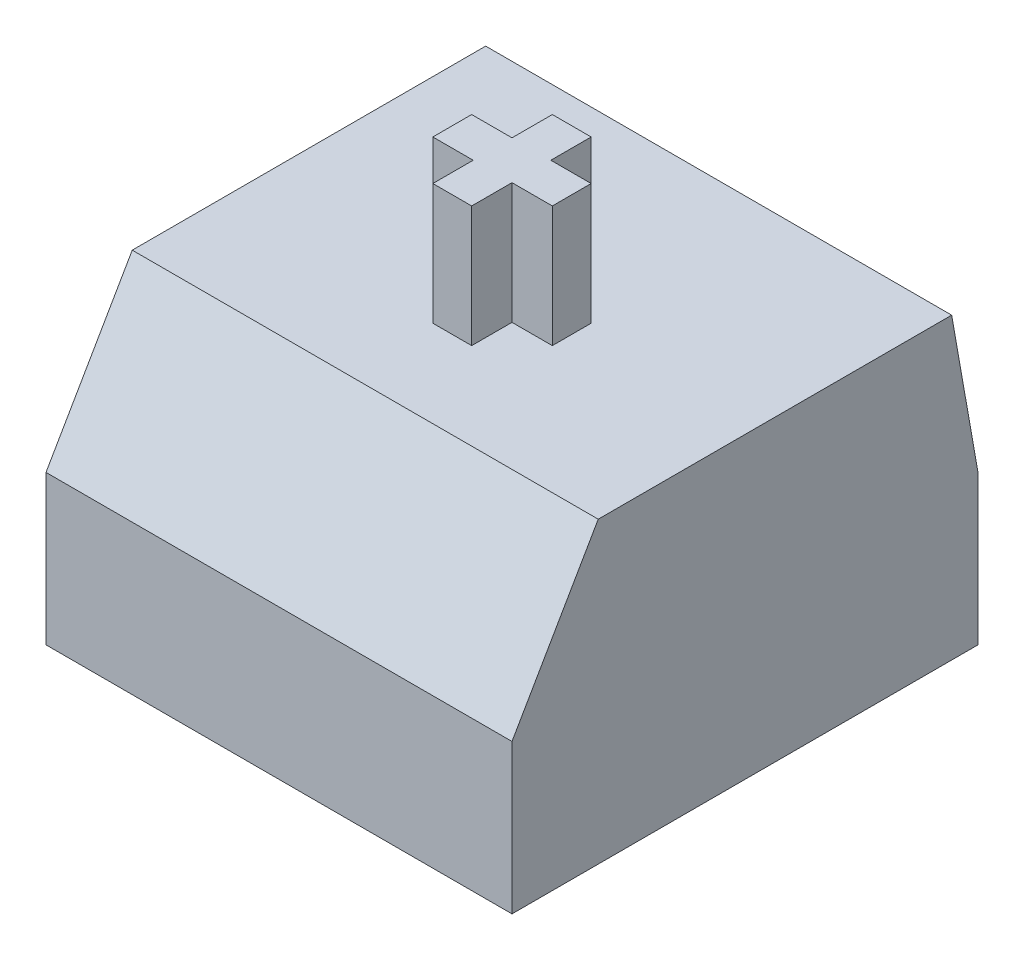
SolidWorks part; units mm, degrees
ref_plane "Front Plane" through (0, 0, 0) normal (0, 0, 1) x (1, 0, 0)
ref_plane "Top Plane" through (0, 0, 0) normal (0, 1, 0) x (1, 0, 0)
ref_plane "Right Plane" through (0, 0, 0) normal (1, 0, 0) x (0, 0, -1)
sketch "Sketch1" plane through (0, 0, 0) normal (0, 1, 0) x (1, 0, 0)
  line L0 (0, -55) -> (0, 55) construction
  line L1 (-7.8, 7.8) -> (7.8, 7.8)
  line L2 (-7.8, 7.8) -> (-7.8, -7.8)
  line L3 (-7.8, -7.8) -> (7.8, -7.8)
  line L4 (7.8, 7.8) -> (7.8, -7.8)
  line L5 (-55, 0) -> (55, 0) construction
  dimension "D1" = 15.6
  dimension "D2" = 15.6
  dimension "D3" = 7.8
  dimension "D4" = 7.8
extrude "Boss-Extrude1" add sketch "Sketch1" along normal blind 5
sketch "Sketch2" plane through (0, 0, 0) normal (1, 0, 0) x (0, 0, -1)
  line L0 (-7.8, 5) -> (7.8, 5)
  line L1 (7.8, 5) -> (6.9184, 10)
  line L2 (6.9184, 10) -> (-4.9132, 10)
  line L3 (-4.9132, 10) -> (-7.8, 5)
  dimension "D1" = 80
  dimension "D2" = 60
  dimension "D3" = 5
extrude "Boss-Extrude2" add sketch "Sketch2" along normal mid plane 15.6 contours L3 L0 L1 L2
sketch "Sketch3" plane through (0, 10, 0) normal (0, 1, 0) x (1, 0, 0)
  line L0 (-0.65, 2) -> (0.65, 2)
  line L1 (0.65, 2) -> (0.65, 0.65)
  line L2 (0.65, 0.65) -> (2, 0.65)
  line L3 (2, 0.65) -> (2, -0.65)
  line L4 (2, -0.65) -> (0.65, -0.65)
  line L5 (0.65, -0.65) -> (0.65, -2)
  line L6 (0.65, -2) -> (-0.65, -2)
  line L7 (-0.65, -2) -> (-0.65, -0.65)
  line L8 (-0.65, -0.65) -> (-2, -0.65)
  line L9 (-2, -0.65) -> (-2, 0.65)
  line L10 (-2, 0.65) -> (-0.65, 0.65)
  line L11 (-0.65, 0.65) -> (-0.65, 2)
  line L12 (0, -5.5) -> (0, 5.5) construction
  line L13 (-5.5, 0) -> (5.5, 0) construction
  point P3 (0, -2)
  dimension "D1" = 1.3
  dimension "D2" = 1.3
  dimension "D3" = 4
  dimension "D4" = 4
  dimension "D5" = 2
  dimension "D6" = 2
  dimension "D7" = 0.65
  dimension "D8" = 0.65
extrude "Boss-Extrude3" add sketch "Sketch3" along normal blind 4.05
sketch "Sketch4" plane through (0, 0, 0) normal (0, 1, 0) x (1, 0, 0)
  circle A0 centre (0, 0) radius 1.925
  dimension "D1" = 3.85
extrude "Boss-Extrude4" add sketch "Sketch4" against normal blind 3
sketch "Sketch6" plane through (0, 0, 0) normal (0, 1, 0) x (1, 0, 0)
  line L0 (0, -8.58) -> (0, 8.58) construction
  line L1 (-8.58, 0) -> (8.58, 0) construction
  circle A0 centre (2.54, 5.08) radius 0.65
  circle A1 centre (-3.81, 2.54) radius 0.65
  dimension "D1" = 1.3
  dimension "D2" = 1.3
  dimension "D3" = 3.81
  dimension "D4" = 2.54
  dimension "D5" = 2.54
  dimension "D6" = 5.08
extrude "Boss-Extrude5" add sketch "Sketch6" against normal blind 4
